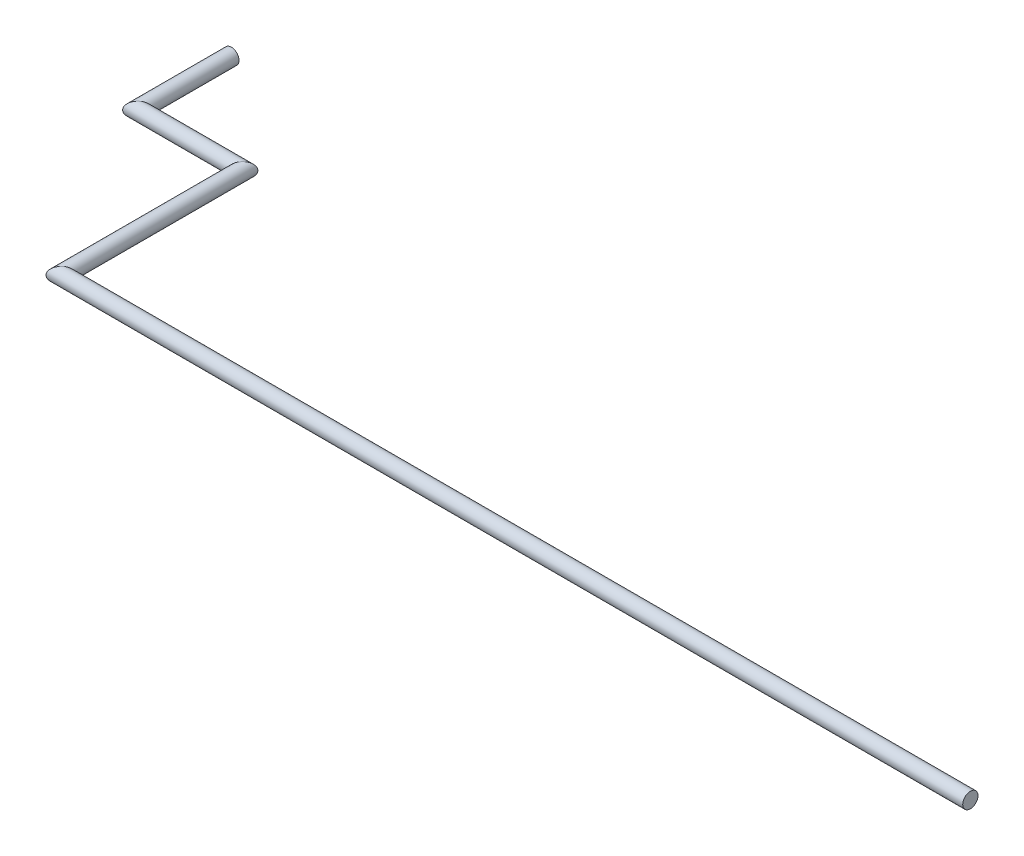
SolidWorks part; units mm, degrees
ref_plane "Front Plane" through (0, 0, 0) normal (0, 0, 1) x (1, 0, 0)
ref_plane "Top Plane" through (0, 0, 0) normal (0, 1, 0) x (1, 0, 0)
ref_plane "Right Plane" through (0, 0, 0) normal (1, 0, 0) x (0, 0, -1)
sketch "Sketch1" plane through (0, 0, 0) normal (0, 1, 0) x (1, 0, 0)
  line L0 (0, 0) -> (-48.387, 0)
  line L1 (-48.387, 0) -> (-48.387, 9.652)
  line L2 (-48.387, 9.652) -> (-53.9623, 9.652)
  line L3 (-53.9623, 9.652) -> (-53.9623, 14.6304)
  dimension "D1" = 48.387
  dimension "D2" = 9.652
  dimension "D3" = 5.5753
  dimension "D4" = 4.9784
sketch "Sketch2" plane through (0, 0, 0) normal (1, 0, 0) x (0, 0, -1)
  circle A0 centre (0, 0) radius 0.4064
  dimension "D1" = 0.8128
sweep "Sweep1" add profiles "Sketch2" path "Sketch1"
